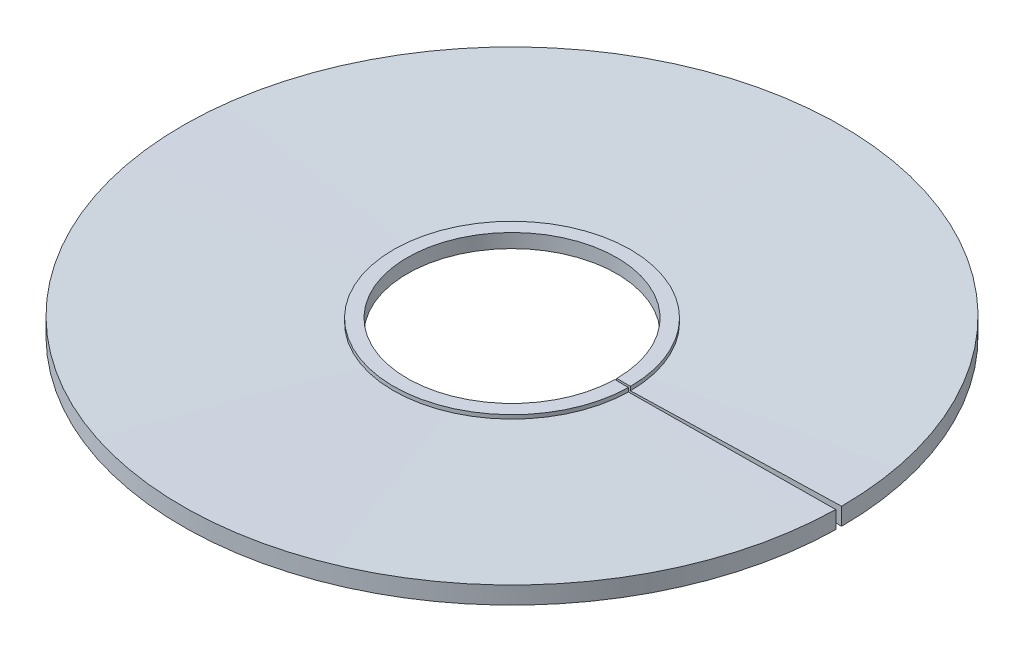
SolidWorks part; units mm, degrees
material "Polypropylene"
ref_plane "Front Plane" through (0, 0, 0) normal (0, 0, 1) x (1, 0, 0)
ref_plane "Top Plane" through (0, 0, 0) normal (0, 1, 0) x (1, 0, 0)
ref_plane "Right Plane" through (0, 0, 0) normal (1, 0, 0) x (0, 0, -1)
sketch "Sketch1" plane through (0, 0, 0) normal (0, 0, 1) x (1, 0, 0)
  line L0 (0, 0) -> (0, 27.6842) construction
  line L1 (43.1, 2.54) -> (38.1, 2.54)
  line L2 (38.1, 2.54) -> (38.1, -2.54)
  line L3 (38.1, -2.54) -> (43.1, -2.54)
  line L4 (43.1, -2.54) -> (43.1, -1.143)
  line L5 (43.1, -1.143) -> (119.888, -3.175)
  line L6 (119.888, -3.175) -> (119.888, 3.175)
  line L7 (119.888, 3.175) -> (43.1, 1.143)
  line L8 (43.1, 1.143) -> (43.1, 2.54)
  line L9 (0, 0) -> (38.1, 0) construction
  line L10 (38.1, 0) -> (119.888, 0) construction
  dimension "D1" = 5.08
  dimension "D2" = 5
  dimension "D3" = 81.788
  dimension "D4" = 6.35
  dimension "D5" = 2.286
  dimension "D6" = 76.2
revolve "Revolve1" add sketch "Sketch1" angle 359 about L0
